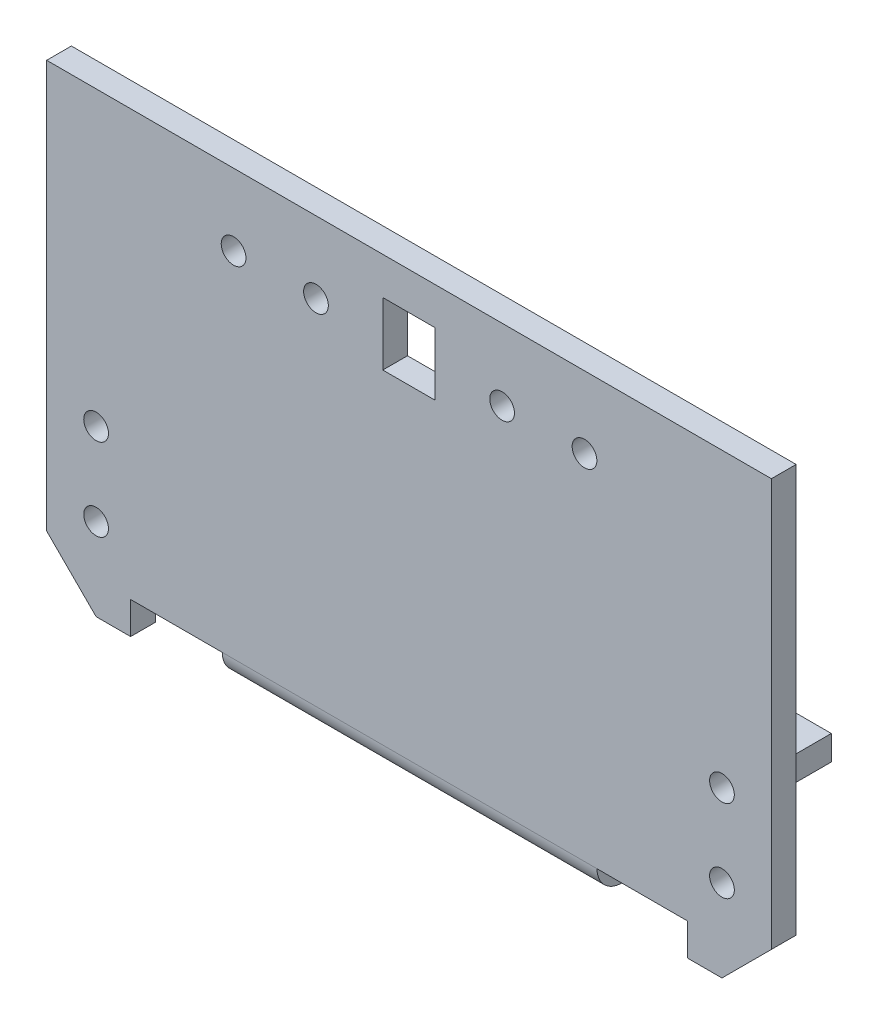
SolidWorks part; units mm, degrees
ref_plane "Front Plane" through (0, 0, 0) normal (0, 0, 1) x (1, 0, 0)
ref_plane "Top Plane" through (0, 0, 0) normal (0, 1, 0) x (1, 0, 0)
ref_plane "Right Plane" through (0, 0, 0) normal (1, 0, 0) x (0, 0, -1)
sketch "Sketch1" plane through (0, 0, 0) normal (0, 0, 1) x (1, 0, 0)
  line L1 (-33.7879, 25.3517) -> (-33.7879, 14.6993) construction
  line L2 (-33.7879, 14.6993) -> (-37.9759, 14.6993) construction
  line L3 (-37.9759, 14.6993) -> (-43.9759, 20.6993) construction
  line L4 (-43.9759, 20.6993) -> (-43.9759, 28.4551) construction
  line L7 (-33.7879, 18.6025) -> (-33.7879, 14.6993)
  line L8 (-33.7879, 14.6993) -> (-37.9759, 14.6993)
  line L9 (-37.9759, 14.6993) -> (-43.9759, 20.6993)
  line L10 (-43.9759, 20.6993) -> (-43.9759, 28.4551)
  line L11 (-43.9759, 28.4551) -> (-43.9759, 70.1751)
  line L14 (33.7879, 18.6025) -> (33.7879, 14.6993)
  line L15 (33.7879, 14.6993) -> (37.9759, 14.6993)
  line L16 (37.9759, 14.6993) -> (43.9759, 20.6993)
  line L17 (43.9759, 20.6993) -> (43.9759, 28.4551)
  line L18 (-43.9759, 70.1751) -> (43.9759, 70.1751)
  line L19 (33.7879, 18.6025) -> (-33.7879, 18.6025)
  line L21 (43.9759, 70.1751) -> (43.9759, 28.4551)
  dimension "D1" = 41.72
extrude "Boss-Extrude1" add sketch "Sketch1" along normal blind 3 contours L21 L17 L16 L15 L14 L19 L7 L8 L9 L10 L11 L18
sketch "Sketch2" plane through (0, 0, 3) normal (0, 0, 1) x (1, 0, 0)
  line L0 (37.9759, 14.6993) -> (37.9759, 24.6993) construction
  line L1 (0, 0) -> (0, 83.7503) construction
  line L3 (21.2938, 63.9782) -> (1.2938, 63.9782) construction
  line L4 (21.2938, 63.9782) -> (21.2938, 61.4782) construction
  circle A0 centre (37.9759, 24.6993) radius 1.5
  circle A2 centre (37.9759, 34.6993) radius 1.5
  circle A3 centre (-37.9759, 24.6993) radius 1.5
  circle A4 centre (-37.9759, 34.6993) radius 1.5
  circle A5 centre (21.2938, 61.4782) radius 1.5
  circle A6 centre (11.2938, 61.4782) radius 1.5
  circle A7 centre (-11.2938, 61.4782) radius 1.5
  circle A8 centre (-21.2938, 61.4782) radius 1.5
  dimension "D2" = 2
  dimension "D3" = 3
  dimension "D4" = 2.5
  dimension "D5" = 20
  dimension "D6" = 3
  dimension "D1" = 10
  dimension "D7" = 2
extrude "Cut-Extrude1" cut sketch "Sketch2" against normal up to surface (3 mm away) up to face at (0, 27.7751, 0)
sketch "Sketch3" plane through (0, 0, 0) normal (0, 0, -1) x (-1, 0, 0)
  line L0 (3.1837, 65.6365) -> (-3.1663, 65.6365)
  line L1 (-3.1663, 65.6365) -> (-3.1663, 58.0165)
  line L2 (-3.1663, 58.0165) -> (3.1837, 58.0165)
  line L3 (3.1837, 58.0165) -> (3.1837, 65.6365)
  dimension "D1" = 7.62
  dimension "D2" = 6.35
extrude "Cut-Extrude2" cut sketch "Sketch3" against normal up to surface (3 mm away) up to face at (22.7938, 61.4782, 3)
sketch "Sketch4" plane through (0, 18.6025, 0) normal (0, -1, 0) x (1, 0, 0)
  line L0 (-12.6851, -20.4341) -> (14.9476, -20.4341)
  line L1 (14.9476, -20.4341) -> (14.9476, -25.4341)
  line L2 (14.9476, -25.4341) -> (22.8153, -25.4341)
  line L3 (-22.6647, 3) -> (-22.6647, -25.4341)
  line L7 (22.8153, 3) -> (22.8153, -25.4341)
  line L12 (-12.6851, -25.4341) -> (-22.6647, -25.4341)
  line L14 (22.8153, 3) -> (-22.6647, 3)
  line L15 (-22.6647, 3) -> (22.8153, 3)
  line L19 (-12.6851, -20.4341) -> (-12.6851, -25.4341)
  dimension "D2" = 45.48
  dimension "D3" = 5
extrude "Boss-Extrude2" add sketch "Sketch4" along normal blind 3
fillet "Fillet2" radius 3 1 edges at (0.0753, 15.6025, 3)
